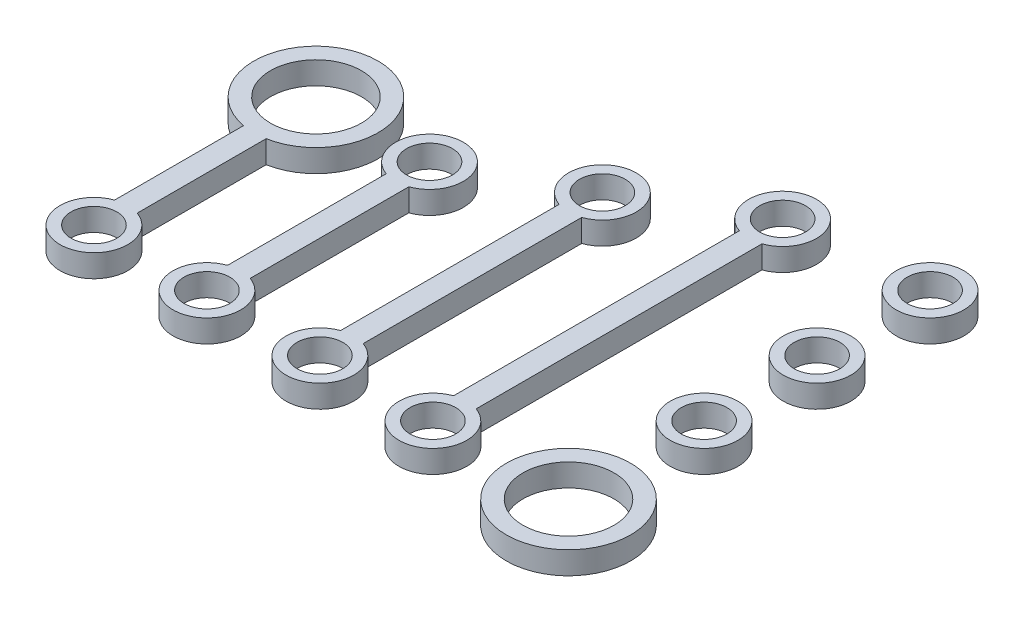
SolidWorks part; units mm, degrees
ref_plane "Спереди" through (0, 0, 0) normal (0, 0, 1) x (1, 0, 0)
ref_plane "Сверху" through (0, 0, 0) normal (0, 1, 0) x (1, 0, 0)
ref_plane "Справа" through (0, 0, 0) normal (1, 0, 0) x (0, 0, -1)
other "Configuration Table"
sketch "Эскиз1" plane through (0, 0, 0) normal (0, 1, 0) x (1, 0, 0)
  line L0 (-24, 0) -> (-24, 61.9) construction
  line L1 (0, 0) -> (-24, 0) construction
  line L2 (-24, 0) -> (-44, 0) construction
  line L3 (-44, 0) -> (-64, 0) construction
  line L4 (-64, 0) -> (-84, 0) construction
  line L5 (-84, 0) -> (-84, 39.3) construction
  line L6 (-64, 0) -> (-64, 39.4) construction
  line L7 (-44, 0) -> (-44, 50) construction
  line L8 (-22, 55.3345) -> (-22, 27.8782) construction
  line L9 (-42, 54.1025) -> (-42, 32.3287) construction
  line L10 (-46, 43.7868) -> (-46, 22.013) construction
  line L11 (-66, 43.5798) -> (-66, 21.806) construction
  line L12 (-62, 40.2676) -> (-62, 18.4938) construction
  line L13 (-86, 41.9237) -> (-86, 20.1499) construction
  line L14 (-82, 41.9237) -> (-82, 20.1499) construction
  line L15 (-26, 32.8152) -> (-26, 11.0414) construction
  line L16 (0, 0) -> (0, 24) construction
  line L17 (-86, 5.6569) -> (-86, 28.4833)
  line L18 (-82, 5.6569) -> (-82, 28.4833)
  line L19 (-66, 33.7431) -> (-66, 5.6569)
  line L20 (-62, 5.6569) -> (-62, 33.7431)
  line L23 (-26, 5.6569) -> (-26, 56.2431)
  line L24 (-22, 56.2431) -> (-22, 5.6569)
  line L25 (-46, 44.3431) -> (-46, 5.6569)
  line L26 (-42, 5.6569) -> (-42, 44.3431)
  line L27 (0, 24) -> (0, 44) construction
  line L28 (0, 44) -> (0, 64) construction
  circle A0 centre (-24, 0) radius 6 construction
  circle A1 centre (-24, 61.9) radius 6 construction
  circle A2 centre (-84, 0) radius 6 construction
  circle A3 centre (-64, 0) radius 6 construction
  circle A4 centre (-44, 0) radius 6 construction
  circle A5 centre (-84, 39.3) radius 11 construction
  circle A6 centre (-64, 39.4) radius 6 construction
  circle A7 centre (-44, 50) radius 6 construction
  circle A8 centre (-84, 39.3) radius 8.05
  circle A9 centre (-84, 0) radius 4.05
  circle A10 centre (-64, 39.4) radius 4.05
  circle A11 centre (-64, 0) radius 4.05
  circle A12 centre (-44, 0) radius 4.05
  circle A13 centre (-24, 0) radius 4.05
  circle A14 centre (-24, 61.9) radius 4.05
  circle A15 centre (-44, 50) radius 4.05
  circle A16 centre (0, 0) radius 8.05
  circle A17 centre (0, 0) radius 11
  circle A18 centre (0, 24) radius 4.05
  circle A19 centre (0, 24) radius 6
  arc A20 (-82, 28.4833) -> (-86, 28.4833) centre (-84, 39.3) ccw
  arc A21 (-86, 5.6569) -> (-82, 5.6569) centre (-84, 0) ccw
  arc A22 (-62, 33.7431) -> (-66, 33.7431) centre (-64, 39.4) ccw
  arc A23 (-66, 5.6569) -> (-62, 5.6569) centre (-64, 0) ccw
  arc A24 (-46, 5.6569) -> (-42, 5.6569) centre (-44, 0) ccw
  arc A26 (-26, 5.6569) -> (-22, 5.6569) centre (-24, 0) ccw
  arc A27 (-22, 56.2431) -> (-26, 56.2431) centre (-24, 61.9) ccw
  arc A28 (-42, 44.3431) -> (-46, 44.3431) centre (-44, 50) ccw
  circle A29 centre (0, 64) radius 6
  circle A30 centre (0, 64) radius 4.05
  circle A31 centre (0, 44) radius 6
  circle A32 centre (0, 44) radius 4.05
  dimension "D1" = 12
  dimension "D2" = 12
  dimension "D3" = 12
  dimension "D4" = 12
  dimension "D6" = 12
  dimension "D7" = 12
  dimension "D8" = 12
  dimension "D22" = 8.1
  dimension "D23" = 8.1
  dimension "D24" = 8.1
  dimension "D25" = 8.1
  dimension "D26" = 8.1
  dimension "D27" = 8.1
  dimension "D28" = 8.1
  dimension "D5" = 16.1
  dimension "D21" = 22
  dimension "D38" = 8.1
  dimension "D39" = 12
  dimension "D40" = 8.1
  dimension "D41" = 12
  dimension "D29" = 16.1
  dimension "D30" = 22
  dimension "D31" = 8.1
  dimension "D32" = 12
  dimension "D9" = 2
  dimension "D10" = 2
  dimension "D11" = 2
  dimension "D12" = 2
  dimension "D13" = 2
  dimension "D14" = 2
  dimension "D15" = 2
  dimension "D16" = 2
  dimension "D17" = 39.3
  dimension "D18" = 39.4
  dimension "D19" = 50
  dimension "D20" = 61.9
  dimension "D33" = 20
  dimension "D34" = 20
  dimension "D35" = 20
  dimension "D36" = 24
  dimension "D37" = 24
  dimension "D42" = 20
  dimension "D43" = 20
extrude "Бобышка-Вытянуть1" add sketch "Эскиз1" along normal blind 4
equation "\"innd\"= 8.1мм"
equation "\"extd\"= 12мм"
equation "\"D1@Эскиз1\"=\"extd\""
equation "\"D2@Эскиз1\"=\"extd\""
equation "\"D3@Эскиз1\"=\"extd\""
equation "\"D4@Эскиз1\"=\"extd\""
equation "\"D6@Эскиз1\"=\"extd\""
equation "\"D8@Эскиз1\"=\"extd\""
equation "\"w\"= 4мм"
equation "\"D9@Эскиз1\"=\"w\"/2"
equation "\"D10@Эскиз1\"=\"w\"/2"
equation "\"D11@Эскиз1\"=\"w\"/2"
equation "\"D12@Эскиз1\"=\"w\"/2"
equation "\"D13@Эскиз1\"=\"w\"/2"
equation "\"D14@Эскиз1\"=\"w\"/2"
equation "\"D15@Эскиз1\"=\"w\"/2"
equation "\"D16@Эскиз1\"=\"w\"/2"
equation "\"D22@Эскиз1\"=\"innd\""
equation "\"D23@Эскиз1\"=\"innd\""
equation "\"D24@Эскиз1\"=\"innd\""
equation "\"D25@Эскиз1\"=\"innd\""
equation "\"D26@Эскиз1\"=\"innd\""
equation "\"D27@Эскиз1\"=\"innd\""
equation "\"D28@Эскиз1\"=\"innd\""
equation "\"D38@Эскиз1\"=\"innd\""
equation "\"D39@Эскиз1\"=\"extd\""
equation "\"D40@Эскиз1\"=\"innd\""
equation "\"D41@Эскиз1\"=\"extd\""
equation "\"D31@Эскиз1\"=\"innd\""
equation "\"D32@Эскиз1\"=\"extd\""
